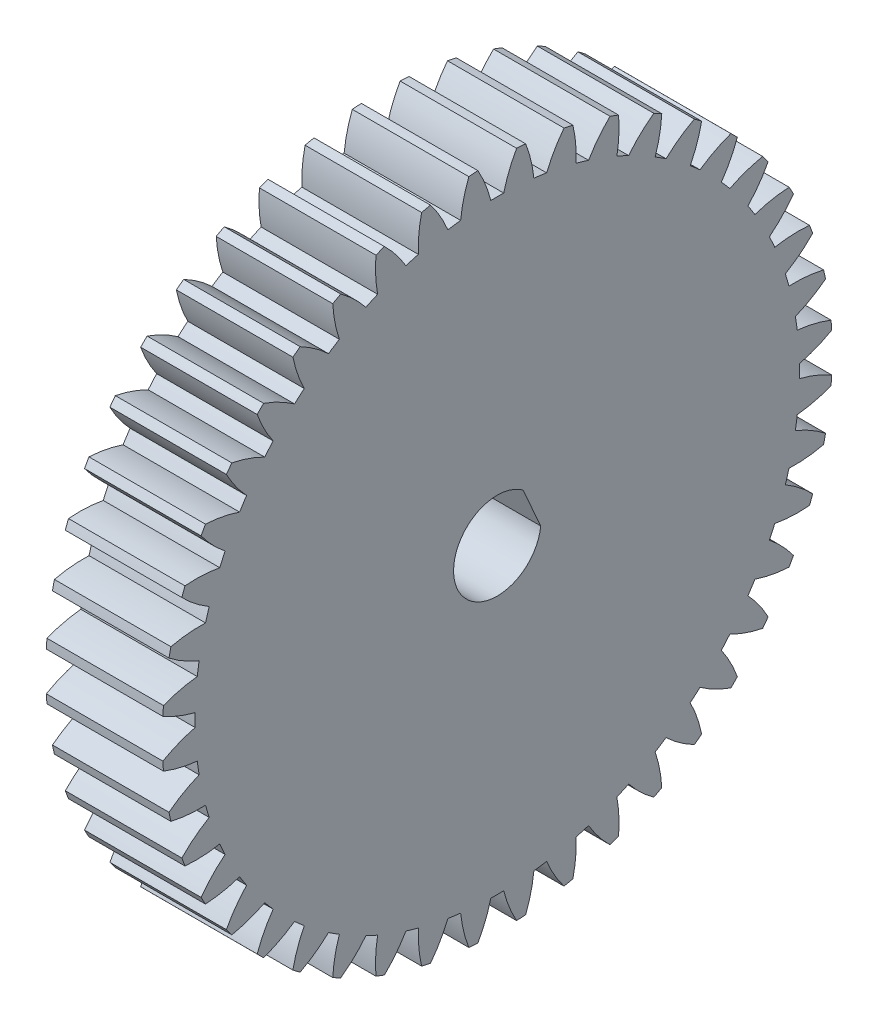
SolidWorks part; units mm, degrees
ref_plane "Plane1" through (0, 0, 0) normal (0, 0, 1) x (1, 0, 0)
ref_plane "Plane2" through (0, 0, 0) normal (0, 1, 0) x (1, 0, 0)
ref_plane "Plane3" through (0, 0, 0) normal (1, 0, 0) x (0, 0, -1)
sketch "HoldingSke" plane through (0, 0, 0) normal (0, 1, 0) x (1, 0, 0)
  line L0 (0, 0) -> (1.4387, -1.3893)
  line L1 (-15, 0) -> (100, 0) construction
  line L2 (0, 0) -> (-2.1039, 2.3779)
  line L3 (0, 0) -> (-11.863, 4.5341)
  line L4 (0, 0) -> (6.2122, 5.9991)
  line L5 (0, 0) -> (-7.0271, -2.6209)
  line L6 (0, 0) -> (-3.3159, -2.2372)
  line L7 (-2.1039, 2.3779) -> (-0.4895, 9.7021)
  line L8 (-76.2, 54.61) -> (-75.7, 54.61)
  line L9 (-71.009, 38.7566) -> (-53.1078, 45.2721)
  line L10 (-76.2, 71.12) -> (104.1128, 71.12)
  line L11 (0, 0) -> (-4, 0)
  line L12 (-76.2, 101.6) -> (-76.181, 101.6)
  line L13 (24.9733, 27.94) -> (52.9518, 28.4284)
  line L14 (24.9733, 27.94) -> (24.9743, 27.94)
  line L15 (24.9733, 27.94) -> (100.4006, 29.5858)
  line L16 (-63.627, -0.5) -> (-12.827, -0.5)
  circle A0 centre (0, 0) radius 1.5
  circle A1 centre (0, 0) radius 2.5
  circle A2 centre (0, 0) radius 2.5
  circle A3 centre (0, 0) radius 1.5
  dimension "MHD" = 5
  dimension "Hub_dia" = 5
  dimension "Bore" = 3
  dimension "MBD" = 3
  dimension "Num_teeth" = 44
  dimension "Pitch" = 2
  dimension "Overall_len" = 7.5
  dimension "Show_teeth" = 44
  dimension "Thickness" = 4
  dimension "OAL" = 7.5001
  dimension "T_dim" = 0.5
  dimension "Ap" = 20
  dimension "H" = 19.05
  dimension "Pitch_radius" = 180.3128
  dimension "Width" = 4
  dimension "Backlash" = 0.019
  dimension "Addendum_fac" = 1
  dimension "Dedendum_fac" = 1.25
  dimension "Clearance_fac" = 0.25
  dimension "Dedendum_add" = 0.001
  dimension "Module" = 0.5
sketch "BasProSke" plane through (0, 0, 0) normal (0, 1, 0) x (1, 0, 0)
  line L0 (-10, 0) -> (60, 0) construction
  line L1 (0, 0) -> (0, 11.5)
  line L2 (0, 0) -> (4, 0)
  line L3 (4, 0) -> (4, 11.5)
  line L4 (4, 11.5) -> (0, 11.5)
  dimension "Thickness" = 4
  dimension "Diameter" = 23
revolve "Base-Revolve" add sketch "BasProSke" angle 360 about L0
sketch "TooCutSke" plane through (0, 0, 0) normal (1, 0, 0) x (0, 0, -1)
  line L1 (0, 0) -> (0, 107) construction
  line L2 (0, 0) -> (-0.4259, 10.9918) construction
  line L3 (0, 0) -> (-1.5686, 21.9322) construction
  line L4 (-0.4259, 10.9918) -> (-0.7843, 10.9661) construction
  arc A0 (0.2217, 10.3716) -> (-0.2217, 10.3716) centre (0, 0) ccw
  arc A1 (0.6787, 11.5054) -> (-0.6787, 11.5054) centre (0, 0) ccw
  circle A2 centre (0, 0) radius 11 construction
  circle A3 centre (0, 0) radius 10.3366 construction
  arc A4 (-0.2217, 10.3716) -> (-0.6787, 11.5054) centre (-4.4917, 9.3097) ccw
  arc A5 (0.6787, 11.5054) -> (0.2217, 10.3716) centre (4.4917, 9.3097) ccw
  dimension "Root_dia" = 20.748
  dimension "Overcut_dia" = 23.0508
  dimension "Pitch_dia" = 22
  dimension "Base_dia" = 20.6732
  dimension "Flank_rad" = 4.4
  dimension "Half_ang" = 4.091
  dimension "Half_CT" = 0.3594
extrude "ToothCut" cut sketch "TooCutSke" along normal through all
fillet "Breaks" [suppressed] radius 0.01
fillet "RootFillets" [suppressed] radius 0.126
pattern_circular "TeethCuts" count 44 over 360 about axis through (0, 0, 0) along (1, 0, 0) of "ToothCut", "RootFillets", "Breaks"
sketch "HubNeaOneSke" plane through (0, 0, 0) normal (-1, 0, 0) x (0, 0, 1)
  circle A0 centre (0, 0) radius 2.5
  dimension "Diameter" = 5
extrude "HubNearOne" add sketch "HubNeaOneSke" along normal blind 3.5001
sketch "HubNeaBotSke" plane through (0, 0, 0) normal (-1, 0, 0) x (0, 0, 1)
  circle A0 centre (0, 0) radius 2.5
  dimension "Diameter" = 5
extrude "HubNearBoth" [suppressed] add sketch "HubNeaBotSke" along normal blind 1.75
ref_plane "FarPln" through (4, 0, 0) normal (1, 0, 0) x (0, 0, -1)
sketch "HubFarSke" plane through (4, 0, 0) normal (1, 0, 0) x (0, 0, -1)
  circle A0 centre (0, 0) radius 2.5
  dimension "Diameter" = 5
extrude "HubFar" [suppressed] add sketch "HubFarSke" along normal blind 1.75
sketch "BorSke" plane through (0, 0, 0) normal (1, 0, 0) x (0, 0, -1)
  circle A0 centre (0, 0) radius 1.5
  dimension "Diameter" = 3
extrude "Bore" cut sketch "BorSke" along normal mid plane 15.0001
sketch "KeySke" plane through (0, 0, 0) normal (1, 0, 0) x (0, 0, -1)
  line L0 (-0.6, 0) -> (-0.6, 2)
  line L1 (-0.6, 2) -> (0.6, 2)
  line L2 (0.6, 2) -> (0.6, 0)
  line L3 (0, 0) -> (0, 34) construction
  line L4 (-0.6, 0) -> (0.6, 0)
  dimension "Offset" = 2
  dimension "Width" = 1.2
extrude "Keyway" [suppressed] cut sketch "KeySke" along normal mid plane 15.0001
pattern_circular "Keyway2" [suppressed] count 2 every 90 about axis through (-10, 0, 0) along (1, 0, 0)
sketch "Sketch1" plane through (4, 0, 0) normal (1, 0, 0) x (0, 0, -1)
  line L0 (0.8845, 1.2115) -> (1.4914, -0.1602)
  arc A0 (1.4914, -0.1602) -> (0.8845, 1.2115) centre (0, 0) ccw
extrude "Boss-Extrude1" add sketch "Sketch1" against normal blind 7.5
equation "' \"Module@HoldingSke\" = 6.35"
equation "' \"Num_teeth@HoldingSke\" = 12"
equation "' \"Ap@HoldingSke\" =  20"
equation "' \"Ap@HoldingSke\" = 20"
equation "' \"Width@HoldingSke\" = 0.5 * 25.4"
equation "' \"Hub_dia@HoldingSke\"= 1 * 25.4"
equation "' \"Hub_dia@HoldingSke\" = 1 * 25.4"
equation "' \"Overall_len@HoldingSke\" = 1.0 * 25.4"
equation "' \"Bore@HoldingSke\" = 0.75 * 25.4"
equation "' \"T_dim@HoldingSke\" = 0.1 * 25.4"
equation "' \"Width@KeySke\" = 0.25 * 25.4"
equation "' \"Show_teeth@HoldingSke\" = 13"
equation "' \"Backlash@HoldingSke\" = 0.009 * 25.4"
equation "' \"Addendum_fac@HoldingSke\" = 1.0"
equation "' \"Dedendum_fac@HoldingSke\" = 1.25"
equation "' \"Dedendum_add@HoldingSke\" = 0.00005 * 25.4"
equation "' \"Clearance_fac@HoldingSke\" = 0.25"
equation "\"Pitch@HoldingSke\" = 1 / \"Module@HoldingSke\""
equation "\"Overcut_dia@TooCutSke\" = (\"Num_teeth@HoldingSke\" + 2 * \"Addendum_fac@HoldingSke\") / \"Pitch@HoldingSke\" + 0.002 * 25.4"
equation "\"Pitch_dia@TooCutSke\" = \"Num_teeth@HoldingSke\" / \"Pitch@HoldingSke\""
equation "\"Base_dia@TooCutSke\" = \"Num_teeth@HoldingSke\" / \"Pitch@HoldingSke\" * cos((\"Ap@HoldingSke\"  * 3.14159265 / 180))"
equation "\"Root_dia@TooCutSke\" = (\"Num_teeth@HoldingSke\" + 2) / \"Pitch@HoldingSke\" - 2 * (\"Addendum_fac@HoldingSke\" + \"Dedendum_fac@HoldingSke\") / \"Pitch@HoldingSke\" - \"Dedendum_add@HoldingSke\" * 2"
equation "\"Half_ang@TooCutSke\" = 180 / \"Num_teeth@HoldingSke\""
equation "\"Half_CT@TooCutSke\" = \"Num_teeth@HoldingSke\" / \"Pitch@HoldingSke\" * sin((3.14159265 / 2 / \"Num_teeth@HoldingSke\")) / 2 - 7 * \"Backlash@HoldingSke\" / 4"
equation "\"Flank_rad@TooCutSke\" = \"Num_teeth@HoldingSke\" / \"Pitch@HoldingSke\" / 5"
equation "\"Radius@RootFillets\" = \"Clearance_fac@HoldingSke\" / \"Pitch@HoldingSke\" + \"Dedendum_add@HoldingSke\""
equation "\"Break_rad@Breaks\" = 0.02 / \"Pitch@HoldingSke\""
equation "\"Thickness@HoldingSke\" = \"Width@HoldingSke\""
equation "\"OAL@HoldingSke\" = \"Thickness@HoldingSke\""
equation "\"MHD@HoldingSke\" = (\"Num_teeth@HoldingSke\" + 2) / \"Pitch@HoldingSke\" - 2 * (\"Addendum_fac@HoldingSke\" + \"Dedendum_fac@HoldingSke\")  / \"Pitch@HoldingSke\" - \"Dedendum_add@HoldingSke\" * 2"
equation "\"MBD@HoldingSke\" = (\"Num_teeth@HoldingSke\" + 2) / \"Pitch@HoldingSke\" - 2 * (\"Addendum_fac@HoldingSke\" + \"Dedendum_fac@HoldingSke\")  / \"Pitch@HoldingSke\" - \"Dedendum_add@HoldingSke\" * 2 - 0.002 * 25.4"
equation "\"MHD@HoldingSke\" = ((sgn( \"MHD@HoldingSke\" - \"Hub_dia@HoldingSke\" )-1)*( \"MHD@HoldingSke\" - \"Hub_dia@HoldingSke\" ))/-2+ \"Hub_dia@HoldingSke\""
equation "\"MBD@HoldingSke\" = ((sgn( \"MBD@HoldingSke\" - \"Bore@HoldingSke\" )-1)*( \"MBD@HoldingSke\" - \"Bore@HoldingSke\" ))/-2+ \"Bore@HoldingSke\""
equation "\"OAL@HoldingSke\" = ((sgn( \"OAL@HoldingSke\" - \"Overall_len@HoldingSke\" )+1)*( \"OAL@HoldingSke\" - \"Overall_len@HoldingSke\" ))/2 + \"Overall_len@HoldingSke\" + 0.000002 * 25.4"
equation "\"Num_teeth@TeethCuts\" = int( \"Show_teeth@HoldingSke\" ) + 1"
equation "\"Num_teeth@TeethCuts\" = ((sgn( \"Num_teeth@TeethCuts\" - \"Num_teeth@HoldingSke\" )-1)*( \"Num_teeth@TeethCuts\" - \"Num_teeth@HoldingSke\" ))/-2+ \"Num_teeth@HoldingSke\""
equation "\"Num_teeth@TeethCuts\" = ((sgn( \"Num_teeth@TeethCuts\" - 2.0)+1)*( \"Num_teeth@TeethCuts\" - 2.0))/2 +2.0"
equation "\"Angle@TeethCuts\" = 360.0 / \"Num_teeth@HoldingSke\""
equation "\"Diameter@BasProSke\" = (\"Num_teeth@HoldingSke\" + 2 * \"Addendum_fac@HoldingSke\") / \"Pitch@HoldingSke\""
equation "\"Thickness@BasProSke\"  = \"Thickness@HoldingSke\""
equation "' \"Fillet_rad@BasProSke\" =  \"Thickness@HoldingSke\" * 0.05"
equation "' \"Fillet_rad@BasProSke\" = \"Thickness@HoldingSke\" * 0.05"
equation "\"MHD@HoldingSke\" = ((sgn( \"MHD@HoldingSke\" - \"Root_dia@TooCutSke\" )-1)*( \"MHD@HoldingSke\" - \"Root_dia@TooCutSke\" ))/-2+ \"Root_dia@TooCutSke\""
equation "\"Diameter@HubNeaOneSke\" = \"MHD@HoldingSke\""
equation "\"Length@HubNearOne\" = \"OAL@HoldingSke\" - \"Thickness@BasProSke\""
equation "\"Diameter@HubNeaBotSke\" = \"MHD@HoldingSke\""
equation "\"Length@HubNearBoth\" = ( \"OAL@HoldingSke\" - \"Thickness@BasProSke\" ) / 2.0"
equation "\"Thickness@FarPln\" = \"Thickness@BasProSke\""
equation "\"Diameter@HubFarSke\" = \"MHD@HoldingSke\""
equation "\"Length@HubFar\" = ( \"OAL@HoldingSke\" - \"Thickness@BasProSke\" ) / 2.0"
equation "\"Diameter@BorSke\" = \"MBD@HoldingSke\""
equation "\"D1@Bore\" = \"OAL@HoldingSke\" * 2.0"
equation "\"D1@Keyway\" = \"OAL@HoldingSke\" * 2.0"
equation "\"Offset@KeySke\" = \"T_dim@HoldingSke\" + \"MBD@HoldingSke\" / 2.0"
